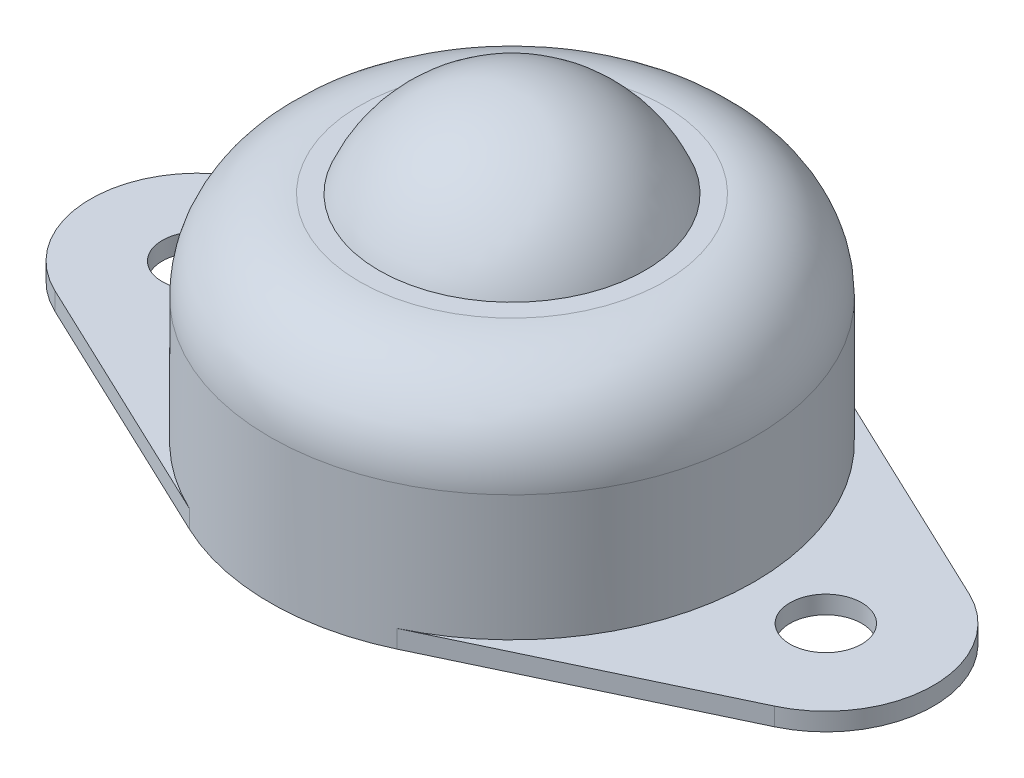
SolidWorks part; units mm, degrees
material "不锈钢 (铁素体)"
ref_plane "前视基准面" through (0, 0, 0) normal (0, 0, 1) x (1, 0, 0)
ref_plane "上视基准面" through (0, 0, 0) normal (0, 1, 0) x (1, 0, 0)
ref_plane "右视基准面" through (0, 0, 0) normal (1, 0, 0) x (0, 0, -1)
other "Configuration Table"
sketch "草图1" plane through (0, 0, 0) normal (0, 1, 0) x (1, 0, 0)
  line L0 (0, 0) -> (0, -30.3591) construction
  line L1 (-20.0714, 5.421) -> (-5.7857, 12.1974)
  line L2 (-20.0714, -5.421) -> (-5.7857, -12.1974)
  line L3 (20.0714, -5.421) -> (5.7857, -12.1974)
  line L4 (20.0714, 5.421) -> (5.7857, 12.1974)
  circle A0 centre (0, 0) radius 13.5 construction
  circle A1 centre (-17.5, 0) radius 6 construction
  circle A2 centre (17.5, 0) radius 6 construction
  arc A3 (-20.0714, 5.421) -> (-20.0714, -5.421) centre (-17.5, 0) ccw
  arc A4 (5.7857, 12.1974) -> (-5.7857, 12.1974) centre (0, 0) ccw
  arc A5 (5.7857, -12.1974) -> (-5.7857, -12.1974) centre (0, 0) cw
  arc A6 (20.0714, 5.421) -> (20.0714, -5.421) centre (17.5, 0) cw
  dimension "D1" = 27
  dimension "D3" = 12
  dimension "D2" = 35
extrude "凸台-拉伸1" add sketch "草图1" along normal blind 1
sketch "草图2" plane through (0, 1, 0) normal (0, 1, 0) x (1, 0, 0)
  circle A0 centre (0, 0) radius 13.5
  dimension "D1" = 27
extrude "凸台-拉伸2" add sketch "草图2" along normal blind 12
sketch "草图4" plane through (0, 0, 0) normal (1, 0, 0) x (0, 0, -1)
  line L0 (0, 0) -> (0, 24.0334) construction
  line L1 (-13.5, 0) -> (-12.1974, 0) construction
  line L2 (0, 18) -> (0, 2)
  arc A0 (0, 18) -> (0, 2) centre (0, 10) ccw
  dimension "D1" = 10
  dimension "D2" = 8
revolve "旋转1" add sketch "草图4" angle 360 about L2
fillet "圆角1" radius 5 1 edges at (0, 13, 13.5)
sketch "草图5" plane through (0, 0, 0) normal (0, -1, 0) x (1, 0, 0)
  circle A0 centre (-17.5, 0) radius 2
  circle A1 centre (17.5, 0) radius 2
  dimension "D1" = 4
extrude "切除-拉伸1" cut sketch "草图5" against normal through all
